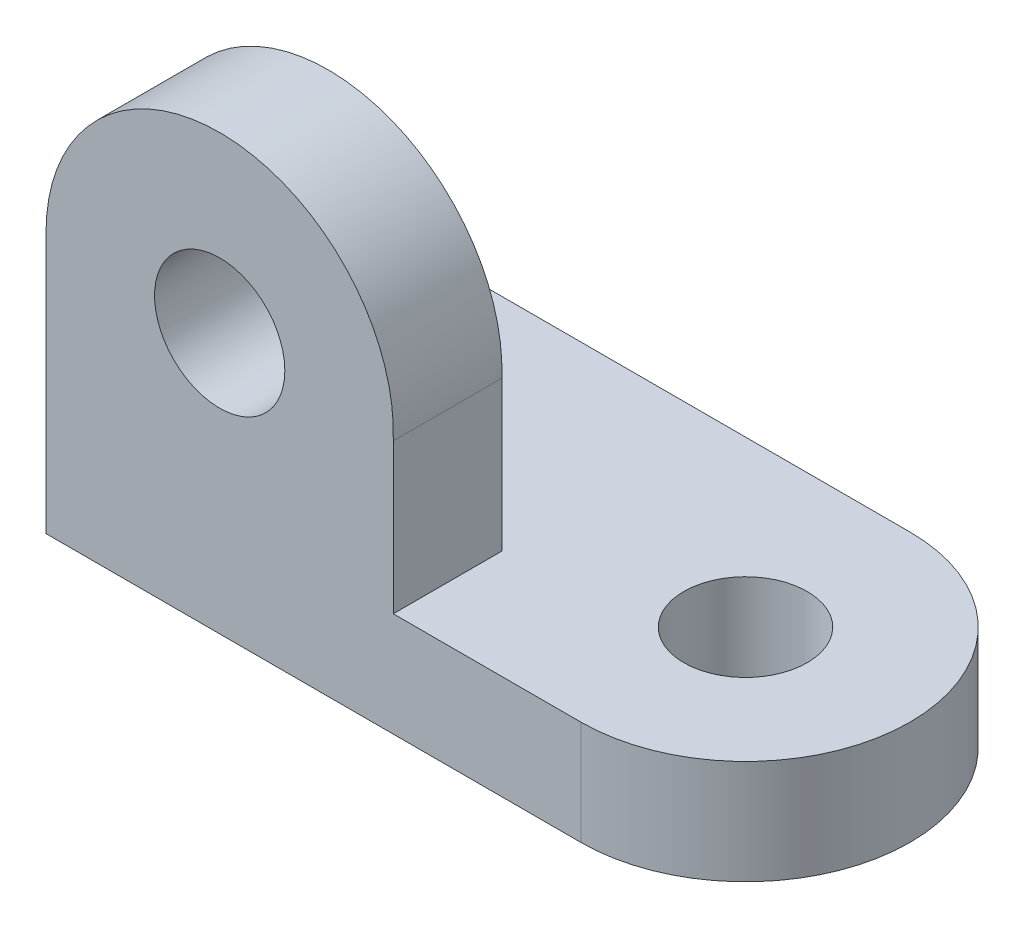
SolidWorks part; units mm, degrees
ref_plane "Front Plane" through (0, 0, 0) normal (0, 0, 1) x (1, 0, 0)
ref_plane "Top Plane" through (0, 0, 0) normal (0, 1, 0) x (1, 0, 0)
ref_plane "Right Plane" through (0, 0, 0) normal (1, 0, 0) x (0, 0, -1)
sketch "Sketch2" plane through (0, 0, 0) normal (0, 1, 0) x (1, 0, 0)
  line L0 (0, 0) -> (0, 75.8031)
  line L1 (0, 0) -> (123.18, 0)
  line L2 (123.18, 75.8031) -> (0, 75.8031)
  arc A0 (123.18, 0) -> (123.18, 75.8031) centre (123.18, 37.9015) ccw
  circle A1 centre (123.18, 37.9015) radius 14.2131
  point P8 (0, 0)
  point P10 (0, 0)
extrude "Boss-Extrude2" add sketch "Sketch2" along normal blind 24
sketch "Sketch4" plane through (0, 0, 0) normal (0, 0, 1) x (1, 0, 0)
  line L0 (0, 24) -> (0, 60)
  line L1 (79.9714, 58.4864) -> (79.9714, 24)
  line L2 (0, 24) -> (123.18, 24) construction
  arc A0 (0, 60) -> (79.9714, 58.4864) centre (40, 60) cw
  circle A1 centre (40, 60) radius 15
  line M3 (123.18, 24) -> (0, 24)
extrude "Boss-Extrude4" add sketch "Sketch4" against normal blind 25 contours A0 L0 L1 A1 M3
fillet "Fillet2" radius 20 1 edges at (0, 12, -75.8031)
